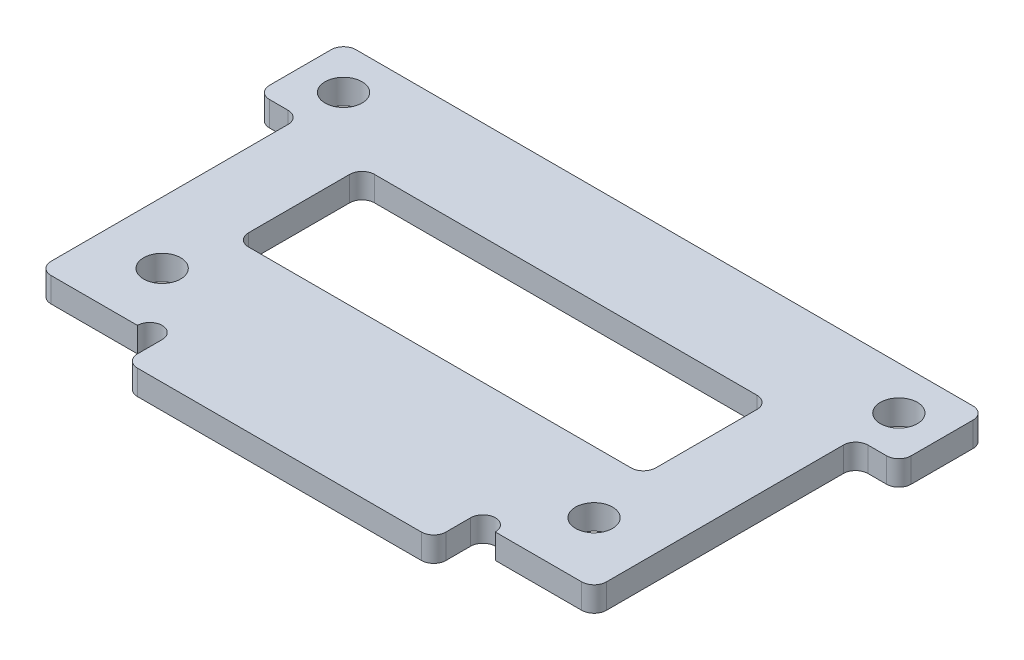
SolidWorks part; units mm, degrees
material "Thornel Mat VMA"
ref_plane "前视基准面" through (0, 0, 0) normal (0, 0, 1) x (1, 0, 0)
ref_plane "上视基准面" through (0, 0, 0) normal (0, 1, 0) x (1, 0, 0)
ref_plane "右视基准面" through (0, 0, 0) normal (1, 0, 0) x (0, 0, -1)
sketch "草图1" plane through (0, 0, 0) normal (0, 1, 0) x (1, 0, 0)
  line L0 (0, -1.1) -> (0, 1.1) construction
  line L2 (-22.5, 3) -> (-22.5, 24.2)
  line L3 (-26, 31.2) -> (26, 31.2)
  line L4 (22.5, 3) -> (22.5, 24.2)
  line L7 (-22.5, 27.7) -> (22.5, 27.7) construction
  line L10 (-12.5, 0) -> (-12.5, 3)
  line L11 (-12.5, 3) -> (-22.5, 3)
  line L14 (12.5, 3) -> (22.5, 3)
  line L15 (12.5, 0) -> (12.5, 3)
  line L17 (-12.5, 0) -> (12.5, 0)
  line L23 (26, 24.2) -> (22.5, 24.2)
  line L25 (26, 24.2) -> (26, 31.2)
  line L26 (-26, 24.2) -> (-22.5, 24.2)
  line L28 (-26, 24.2) -> (-26, 31.2)
  circle A1 centre (-22.5, 27.7) radius 1.5
  circle A2 centre (22.5, 27.7) radius 1.5
  circle A4 centre (-17.5, 8) radius 1.5
  circle A5 centre (17.5, 8) radius 1.5
  dimension "D5" = 3.5
  dimension "D6" = 3.5
  dimension "D10" = 3
  dimension "D11" = 3
  dimension "D12" = 3.5
  dimension "D3" = 5
  dimension "D4" = 5
  dimension "D2" = 45
  dimension "D7" = 3
  dimension "D8" = 24.7
  dimension "D9" = 25
  dimension "D14" = 10
extrude "凸台-拉伸1" add sketch "草图1" along normal blind 2
sketch "草图2" plane through (0, 2, 0) normal (0, 1, 0) x (1, 0, 0)
  line L0 (26, 31.2) -> (-26, 31.2) construction
  line L2 (0, -1.1) -> (0, 1.1) construction
  line L3 (-22.5, 3) -> (-12.5, 3) construction
  line L4 (-16.5, 23.2) -> (16.5, 23.2)
  line L5 (-16.5, 23.2) -> (-16.5, 13)
  line L6 (-16.5, 13) -> (16.5, 13)
  line L7 (16.5, 23.2) -> (16.5, 13)
  line L10 (-22.5, 24.2) -> (-22.5, 3) construction
  line L11 (22.5, 3) -> (22.5, 24.2) construction
  circle A1 centre (-13.5, 3) radius 1
  circle A2 centre (13.5, 3) radius 1
  dimension "D1" = 2
  dimension "D2" = 8
  dimension "D3" = 6
  dimension "D4" = 6
  dimension "D5" = 10
extrude "切除-拉伸1" cut sketch "草图2" against normal through all
fillet "圆角1" radius 1 14 edges at (16.5, 1, -13) (16.5, 1, -23.2) (-16.5, 1, -23.2) (-16.5, 1, -13) (22.5, 1, -3) (-22.5, 1, -3) (12.5, 1, 0) (-12.5, 1, 0) (-26, 1, -31.2) (26, 1, -31.2) (26, 1, -24.2) (22.5, 1, -24.2) (-22.5, 1, -24.2) (-26, 1, -24.2)
